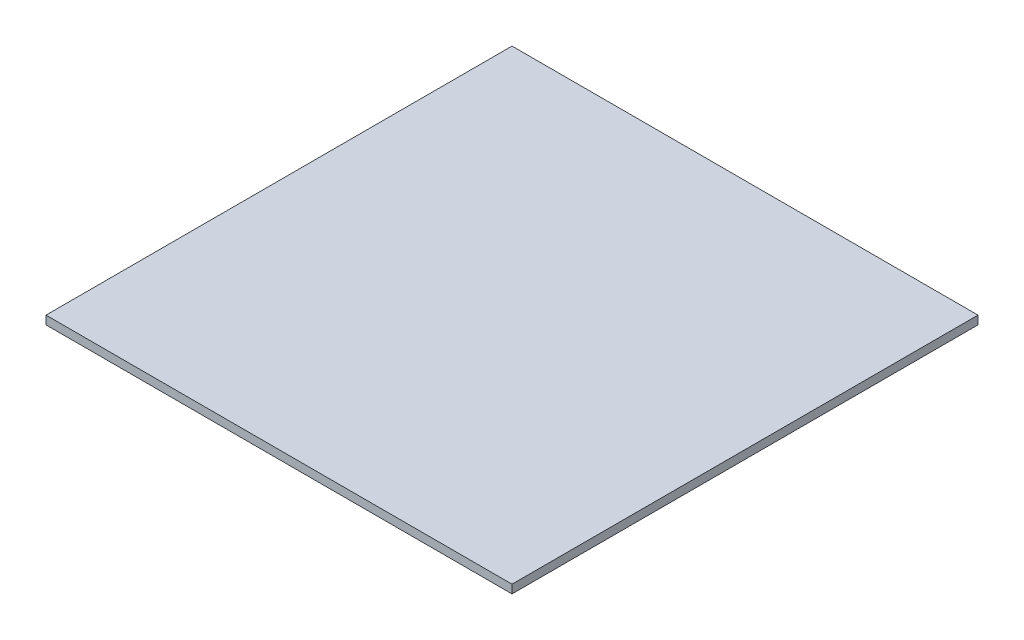
SolidWorks part; units mm, degrees
ref_plane "Alzado" through (0, 0, 0) normal (0, 0, 1) x (1, 0, 0)
ref_plane "Planta" through (0, 0, 0) normal (0, 1, 0) x (1, 0, 0)
ref_plane "Vista lateral" through (0, 0, 0) normal (1, 0, 0) x (0, 0, -1)
sketch "Croquis1" plane through (0, 0, 0) normal (0, 0, 1) x (1, 0, 0)
  line L1 (-55, -1) -> (55, -1)
  line L2 (-55, -1) -> (-55, 1)
  line L3 (-55, 1) -> (55, 1)
  line L4 (55, -1) -> (55, 1)
  line L5 (-55, -1) -> (55, 1) construction
  line L6 (-55, 1) -> (55, -1) construction
  point P0 (0, 0)
  dimension "D1" = 2
  dimension "D2" = 110
extrude "Saliente-Extruir1" add sketch "Croquis1" along normal mid plane 110
